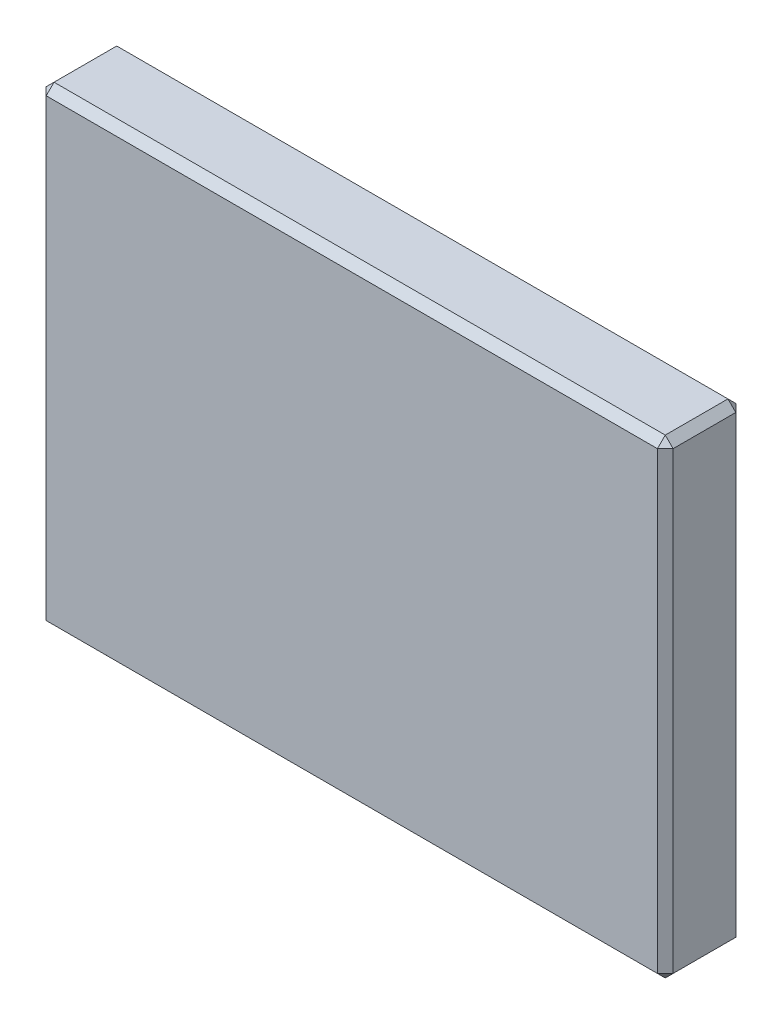
SolidWorks part; units mm, degrees
ref_plane "Front Plane" through (0, 0, 0) normal (0, 0, 1) x (1, 0, 0)
ref_plane "Top Plane" through (0, 0, 0) normal (0, 1, 0) x (1, 0, 0)
ref_plane "Right Plane" through (0, 0, 0) normal (1, 0, 0) x (0, 0, -1)
sketch "Sketch1" plane through (0, 0, 0) normal (0, 0, 1) x (1, 0, 0)
  line L1 (0, 0) -> (101.6, 0)
  line L2 (0, 0) -> (0, 76.2)
  line L3 (0, 76.2) -> (101.6, 76.2)
  line L4 (101.6, 0) -> (101.6, 76.2)
extrude "Boss-Extrude1" add sketch "Sketch1" along normal blind 12.7
chamfer "Chamfer1" distance 1.27 angle 45 12 edges at (0, 38.1, 0) (50.8, 0, 0) (101.6, 38.1, 0) (50.8, 76.2, 0) (0, 38.1, 12.7) (0, 76.2, 6.35) (50.8, 76.2, 12.7) (101.6, 76.2, 6.35) (101.6, 38.1, 12.7) (101.6, 0, 6.35) (50.8, 0, 12.7) (0, 0, 6.35)
